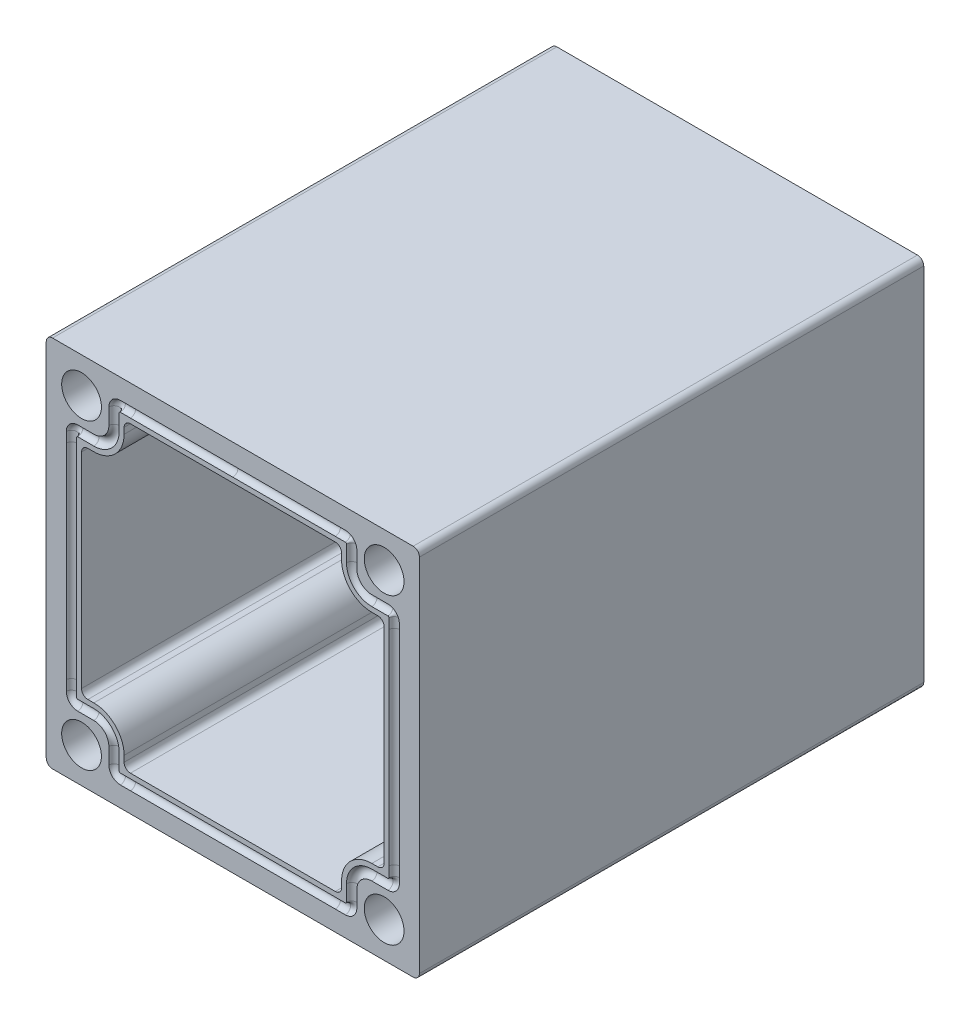
SolidWorks part; units mm, degrees
ref_plane "Front Plane" through (0, 0, 0) normal (0, 0, 1) x (1, 0, 0)
ref_plane "Top Plane" through (0, 0, 0) normal (0, 1, 0) x (1, 0, 0)
ref_plane "Right Plane" through (0, 0, 0) normal (1, 0, 0) x (0, 0, -1)
sketch "Sketch1" plane through (0, 0, 0) normal (0, 0, 1) x (1, 0, 0)
  line L9 (23.495, 22.7012) -> (23.495, -22.7012)
  line L14 (22.7012, -23.495) -> (-22.7012, -23.495)
  line L15 (-23.495, -22.7012) -> (-23.495, 22.7012)
  line L16 (-22.7012, 23.495) -> (22.7012, 23.495)
  line L28 (-20.32, -12.8968) -> (-20.32, -14.1668) construction
  line L34 (-14.1669, -20.32) -> (-12.8969, -20.32) construction
  line L51 (-12.8969, -20.32) -> (12.8968, -20.32) construction
  line L54 (20.32, -12.8969) -> (20.32, 12.8968) construction
  line L57 (12.8969, 20.32) -> (-12.8968, 20.32) construction
  line L60 (-20.32, 12.8969) -> (-20.32, -12.8968) construction
  line L63 (-19.5262, -14.9606) -> (-17.5006, -14.9606) construction
  line L64 (-12.8969, -19.05) -> (12.8968, -19.05)
  line L65 (-13.6906, 18.2563) -> (-13.6906, 17.5006)
  line L66 (-17.5006, 13.6906) -> (-18.2562, 13.6906)
  line L67 (18.2563, 13.6906) -> (17.5006, 13.6906)
  line L68 (13.6906, 17.5006) -> (13.6906, 18.2562)
  line L69 (13.6906, -18.2563) -> (13.6906, -17.5006)
  line L70 (17.5006, -13.6906) -> (18.2562, -13.6906)
  line L71 (-14.9606, -17.5006) -> (-14.9606, -19.5262) construction
  line L73 (-12.8968, 20.32) -> (-14.1668, 20.32) construction
  line L74 (-14.9606, 19.5262) -> (-14.9606, 17.5006) construction
  line L75 (-17.5006, 14.9606) -> (-19.5262, 14.9606) construction
  line L76 (-20.32, 14.1669) -> (-20.32, 12.8969) construction
  line L77 (20.32, 12.8968) -> (20.32, 14.1668) construction
  line L78 (19.5263, 14.9606) -> (17.5006, 14.9606) construction
  line L79 (14.9606, 17.5006) -> (14.9606, 19.5262) construction
  line L80 (14.1669, 20.32) -> (12.8969, 20.32) construction
  line L81 (12.8968, -20.32) -> (14.1668, -20.32) construction
  line L82 (14.9606, -19.5263) -> (14.9606, -17.5006) construction
  line L83 (17.5006, -14.9606) -> (19.5262, -14.9606) construction
  line L84 (20.32, -14.1669) -> (20.32, -12.8969) construction
  line L85 (-18.2563, -13.6906) -> (-17.5006, -13.6906)
  line L86 (-13.6906, -17.5006) -> (-13.6906, -18.2562)
  line L90 (19.05, -12.8969) -> (19.05, 12.8968)
  line L93 (12.8969, 19.05) -> (-12.8968, 19.05)
  line L97 (-19.05, 12.8969) -> (-19.05, -12.8968)
  circle A0 centre (0, 0) radius 19.05 construction
  circle A13 centre (-19.05, -19.05) radius 2.5019 construction
  circle A14 centre (-19.05, 19.05) radius 2.5019 construction
  circle A15 centre (19.05, 19.05) radius 2.5019 construction
  circle A16 centre (19.05, -19.05) radius 2.5019 construction
  circle A17 centre (19.05, -19.05) radius 4.0894 construction
  arc A50 (-13.6906, -17.5006) -> (-17.5006, -13.6906) centre (-17.5006, -17.5006) ccw
  arc A51 (-12.8969, -19.05) -> (-13.6906, -18.2562) centre (-12.8969, -18.2562) cw
  arc A52 (-18.2563, -13.6906) -> (-19.05, -12.8968) centre (-18.2563, -12.8968) cw
  arc A53 (-13.6906, 18.2563) -> (-12.8968, 19.05) centre (-12.8968, 18.2563) cw
  arc A54 (-17.5006, 13.6906) -> (-13.6906, 17.5006) centre (-17.5006, 17.5006) ccw
  arc A55 (-19.05, 12.8969) -> (-18.2562, 13.6906) centre (-18.2562, 12.8969) cw
  arc A56 (18.2563, 13.6906) -> (19.05, 12.8968) centre (18.2563, 12.8968) cw
  arc A57 (13.6906, 17.5006) -> (17.5006, 13.6906) centre (17.5006, 17.5006) ccw
  arc A58 (12.8969, 19.05) -> (13.6906, 18.2562) centre (12.8969, 18.2562) cw
  arc A59 (13.6906, -18.2563) -> (12.8968, -19.05) centre (12.8968, -18.2563) cw
  arc A60 (17.5006, -13.6906) -> (13.6906, -17.5006) centre (17.5006, -17.5006) ccw
  arc A61 (19.05, -12.8969) -> (18.2562, -13.6906) centre (18.2562, -12.8969) cw
  arc A62 (-14.9606, -17.5006) -> (-17.5006, -14.9606) centre (-17.5006, -17.5006) ccw construction
  arc A63 (-14.1669, -20.32) -> (-14.9606, -19.5262) centre (-14.1669, -19.5262) cw construction
  arc A64 (-20.32, -14.1668) -> (-19.5262, -14.9606) centre (-19.5262, -14.1668) ccw construction
  arc A65 (-14.1668, 20.32) -> (-14.9606, 19.5262) centre (-14.1668, 19.5262) ccw construction
  arc A66 (-17.5006, 14.9606) -> (-14.9606, 17.5006) centre (-17.5006, 17.5006) ccw construction
  arc A67 (-20.32, 14.1669) -> (-19.5262, 14.9606) centre (-19.5262, 14.1669) cw construction
  arc A68 (20.32, 14.1668) -> (19.5263, 14.9606) centre (19.5263, 14.1668) ccw construction
  arc A69 (14.9606, 17.5006) -> (17.5006, 14.9606) centre (17.5006, 17.5006) ccw construction
  arc A70 (14.1669, 20.32) -> (14.9606, 19.5262) centre (14.1669, 19.5262) cw construction
  arc A71 (14.1668, -20.32) -> (14.9606, -19.5263) centre (14.1668, -19.5263) ccw construction
  arc A72 (17.5006, -14.9606) -> (14.9606, -17.5006) centre (17.5006, -17.5006) ccw construction
  arc A73 (20.32, -14.1669) -> (19.5262, -14.9606) centre (19.5262, -14.1669) cw construction
  arc A74 (-22.7012, -23.495) -> (-23.495, -22.7012) centre (-22.7013, -22.7013) cw
  arc A75 (22.7012, -23.495) -> (23.495, -22.7012) centre (22.7012, -22.7012) ccw
  arc A76 (23.495, 22.7012) -> (22.7012, 23.495) centre (22.7012, 22.7013) ccw
  arc A77 (-23.495, 22.7012) -> (-22.7012, 23.495) centre (-22.7013, 22.7012) cw
  point P29 (0, 0)
  point P32 (0, 0)
  point P33 (0, 0)
  point P42 (0, 0)
  point P45 (19.05, -14.9606)
  point P57 (14.9606, -19.05)
  point P82 (0, 0)
  point P89 (0, 0)
  point P140 (0, 0)
  dimension "D1" = 38.1
  dimension "D2" = 3.175
  dimension "D3" = 3.175
  dimension "D5" = 4
  dimension "D6" = 1.5875
  dimension "D8" = 5.0038
  dimension "D9" = 0.7937
  dimension "D7" = 3.81
  dimension "D4" = 2.54
  dimension "D14" = 0.7937
  dimension "D11" = 0.7937
  dimension "D12" = 3.175
  dimension "D13" = 3.175
  dimension "D15" = 4
  dimension "D10" = 4
extrude "Boss-Extrude1" add sketch "Sketch1" against normal blind 63.5
sketch "Sketch4" [suppressed] plane through (0, 0, 0) normal (1, 0, 0) x (0, 0, -1)
  line L0 (0, 38.1462) -> (65.278, 38.1462) construction
  line L3 (0, 0) -> (65.278, 0) construction
  line L5 (0, -29.86) -> (65.278, -29.86) construction
  line L6 (0, 52.7974) -> (0, 23.495) construction
  line L7 (65.278, 52.7974) -> (65.278, 23.495) construction
  line L8 (0, -36.225) -> (0, -23.495) construction
  line L9 (65.278, -36.225) -> (65.278, -23.495) construction
  line L10 (65.278, -23.495) -> (65.278, 23.495) construction
  circle A0 centre (12.7, 38.1306) radius 3.9688
  circle A1 centre (52.578, 38.1306) radius 3.9687
  circle A2 centre (10.6423, -36.7905) radius 3.9688
  circle A3 centre (54.6357, -36.7905) radius 3.9687
  dimension "D1" = 12.7
  dimension "D3" = 7.9375
  dimension "D4" = 7.9375
  dimension "D2" = 12.7
  dimension "D5" = 12.7
  dimension "D6" = 12.7
extrude "Cut-Extrude2" [suppressed] cut sketch "Sketch4" along normal through all contours A1 | A0 | A3 | A2
sketch "Sketch7" plane through (0, 0, 0) normal (1, 0, 0) x (0, 0, -1)
  circle A0 centre (0, 20.32) radius 0.65
  dimension "D1" = 1.3
sketch "Sketch11" plane through (0, 0, 0) normal (0, 0, 1) x (1, 0, 0)
  line L0 (-14.9606, 19.5262) -> (-14.9606, 17.5006) construction
  line L1 (-12.8968, 20.32) -> (-14.1668, 20.32) construction
  line L2 (12.8969, 20.32) -> (-12.8968, 20.32) construction
  line L3 (14.1669, 20.32) -> (12.8969, 20.32) construction
  line L4 (14.9606, 17.5006) -> (14.9606, 19.5262) construction
  line L5 (19.5263, 14.9606) -> (17.5006, 14.9606) construction
  line L6 (20.32, 12.8968) -> (20.32, 14.1668) construction
  line L7 (20.32, -12.8969) -> (20.32, 12.8968) construction
  line L8 (20.32, -14.1669) -> (20.32, -12.8969) construction
  line L9 (17.5006, -14.9606) -> (19.5262, -14.9606) construction
  line L10 (14.9606, -19.5263) -> (14.9606, -17.5006) construction
  line L11 (12.8968, -20.32) -> (14.1668, -20.32) construction
  line L12 (-12.8969, -20.32) -> (12.8968, -20.32) construction
  line L13 (-14.1669, -20.32) -> (-12.8969, -20.32) construction
  line L14 (-14.9606, -17.5006) -> (-14.9606, -19.5262) construction
  line L15 (-19.5262, -14.9606) -> (-17.5006, -14.9606) construction
  line L16 (-20.32, -12.8968) -> (-20.32, -14.1668) construction
  line L17 (-20.32, 12.8969) -> (-20.32, -12.8968) construction
  line L18 (-20.32, 14.1669) -> (-20.32, 12.8969) construction
  line L19 (-17.5006, 14.9606) -> (-19.5262, 14.9606) construction
  line L20 (-14.9606, 19.5262) -> (-14.9606, 17.5006)
  line L21 (-12.8968, 20.32) -> (-14.1668, 20.32)
  line L22 (12.8969, 20.32) -> (-12.8968, 20.32)
  line L23 (14.1669, 20.32) -> (12.8969, 20.32)
  line L24 (14.9606, 17.5006) -> (14.9606, 19.5262)
  line L25 (19.5263, 14.9606) -> (17.5006, 14.9606)
  line L26 (20.32, 12.8968) -> (20.32, 14.1668)
  line L27 (20.32, -12.8969) -> (20.32, 12.8968)
  line L28 (20.32, -14.1669) -> (20.32, -12.8969)
  line L29 (17.5006, -14.9606) -> (19.5262, -14.9606)
  line L30 (14.9606, -19.5263) -> (14.9606, -17.5006)
  line L31 (12.8968, -20.32) -> (14.1668, -20.32)
  line L32 (-12.8969, -20.32) -> (12.8968, -20.32)
  line L33 (-14.1669, -20.32) -> (-12.8969, -20.32)
  line L34 (-14.9606, -17.5006) -> (-14.9606, -19.5262)
  line L35 (-19.5262, -14.9606) -> (-17.5006, -14.9606)
  line L36 (-20.32, -12.8968) -> (-20.32, -14.1668)
  line L37 (-20.32, 12.8969) -> (-20.32, -12.8968)
  line L38 (-20.32, 14.1669) -> (-20.32, 12.8969)
  line L39 (-17.5006, 14.9606) -> (-19.5262, 14.9606)
  arc A0 (-14.1668, 20.32) -> (-14.9606, 19.5262) centre (-14.1668, 19.5262) ccw construction
  arc A1 (14.9606, 19.5262) -> (14.1669, 20.32) centre (14.1669, 19.5262) ccw construction
  arc A2 (14.9606, 17.5006) -> (17.5006, 14.9606) centre (17.5006, 17.5006) ccw construction
  arc A3 (20.32, 14.1668) -> (19.5263, 14.9606) centre (19.5263, 14.1668) ccw construction
  arc A4 (19.5262, -14.9606) -> (20.32, -14.1669) centre (19.5262, -14.1669) ccw construction
  arc A5 (17.5006, -14.9606) -> (14.9606, -17.5006) centre (17.5006, -17.5006) ccw construction
  arc A6 (14.1668, -20.32) -> (14.9606, -19.5263) centre (14.1668, -19.5263) ccw construction
  arc A7 (-14.9606, -19.5262) -> (-14.1669, -20.32) centre (-14.1669, -19.5262) ccw construction
  arc A8 (-14.9606, -17.5006) -> (-17.5006, -14.9606) centre (-17.5006, -17.5006) ccw construction
  arc A9 (-20.32, -14.1668) -> (-19.5262, -14.9606) centre (-19.5262, -14.1668) ccw construction
  arc A10 (-19.5262, 14.9606) -> (-20.32, 14.1669) centre (-19.5262, 14.1669) ccw construction
  arc A11 (-17.5006, 14.9606) -> (-14.9606, 17.5006) centre (-17.5006, 17.5006) ccw construction
  arc A12 (-14.1668, 20.32) -> (-14.9606, 19.5262) centre (-14.1668, 19.5262) ccw
  arc A13 (14.9606, 19.5262) -> (14.1669, 20.32) centre (14.1669, 19.5262) ccw
  arc A14 (14.9606, 17.5006) -> (17.5006, 14.9606) centre (17.5006, 17.5006) ccw
  arc A15 (20.32, 14.1668) -> (19.5263, 14.9606) centre (19.5263, 14.1668) ccw
  arc A16 (19.5262, -14.9606) -> (20.32, -14.1669) centre (19.5262, -14.1669) ccw
  arc A17 (17.5006, -14.9606) -> (14.9606, -17.5006) centre (17.5006, -17.5006) ccw
  arc A18 (14.1668, -20.32) -> (14.9606, -19.5263) centre (14.1668, -19.5263) ccw
  arc A19 (-14.9606, -19.5262) -> (-14.1669, -20.32) centre (-14.1669, -19.5262) ccw
  arc A20 (-14.9606, -17.5006) -> (-17.5006, -14.9606) centre (-17.5006, -17.5006) ccw
  arc A21 (-20.32, -14.1668) -> (-19.5262, -14.9606) centre (-19.5262, -14.1668) ccw
  arc A22 (-19.5262, 14.9606) -> (-20.32, 14.1669) centre (-19.5262, 14.1669) ccw
  arc A23 (-17.5006, 14.9606) -> (-14.9606, 17.5006) centre (-17.5006, 17.5006) ccw
sweep "Cut-Sweep2" cut profiles "Sketch7" path "Sketch11"
sketch "Sketch10" plane through (0, 0, 0) normal (0, 0, 1) x (1, 0, 0)
  circle A0 centre (19.05, 19.05) radius 2.5019 construction
  circle A1 centre (19.05, -19.05) radius 2.5019 construction
  circle A2 centre (-19.05, -19.05) radius 2.5019 construction
  circle A3 centre (-19.05, 19.05) radius 2.5019 construction
  circle A4 centre (19.05, 19.05) radius 2.5019
  circle A5 centre (19.05, -19.05) radius 2.5019
  circle A6 centre (-19.05, -19.05) radius 2.5019
  circle A7 centre (-19.05, 19.05) radius 2.5019
extrude "Cut-Extrude3" cut sketch "Sketch10" against normal blind 12.7
sketch "Sketch12" plane through (0, 0, 0) normal (0, 0, 1) x (1, 0, 0)
  line L0 (23.495, 22.7012) -> (23.495, -22.7012) construction
  line L1 (22.7012, -23.495) -> (-22.7012, -23.495) construction
  line L2 (-23.495, -22.7012) -> (-23.495, 22.7012) construction
  line L3 (-22.7012, 23.495) -> (22.7012, 23.495) construction
  line L4 (23.495, 22.7012) -> (23.495, -22.7012)
  line L5 (22.7012, -23.495) -> (-22.7012, -23.495)
  line L6 (-23.495, -22.7012) -> (-23.495, 22.7012)
  line L7 (-22.7012, 23.495) -> (22.7012, 23.495)
  arc A0 (23.495, 22.7012) -> (22.7012, 23.495) centre (22.7012, 22.7013) ccw construction
  arc A1 (22.7012, -23.495) -> (23.495, -22.7012) centre (22.7012, -22.7012) ccw construction
  arc A2 (-23.495, -22.7012) -> (-22.7012, -23.495) centre (-22.7013, -22.7013) ccw construction
  arc A3 (-22.7012, 23.495) -> (-23.495, 22.7012) centre (-22.7013, 22.7012) ccw construction
  arc A4 (23.495, 22.7012) -> (22.7012, 23.495) centre (22.7012, 22.7013) ccw
  arc A5 (22.7012, -23.495) -> (23.495, -22.7012) centre (22.7012, -22.7012) ccw
  arc A6 (-23.495, -22.7012) -> (-22.7012, -23.495) centre (-22.7013, -22.7013) ccw
  arc A7 (-22.7012, 23.495) -> (-23.495, 22.7012) centre (-22.7013, 22.7012) ccw
  circle A8 centre (0, 0) radius 10.414
  dimension "D1" = 20.828
extrude "Boss-Extrude2" add sketch "Sketch12" along normal blind 3.175 from surface at -63.5 starting at face at (0, 0, -63.5)
